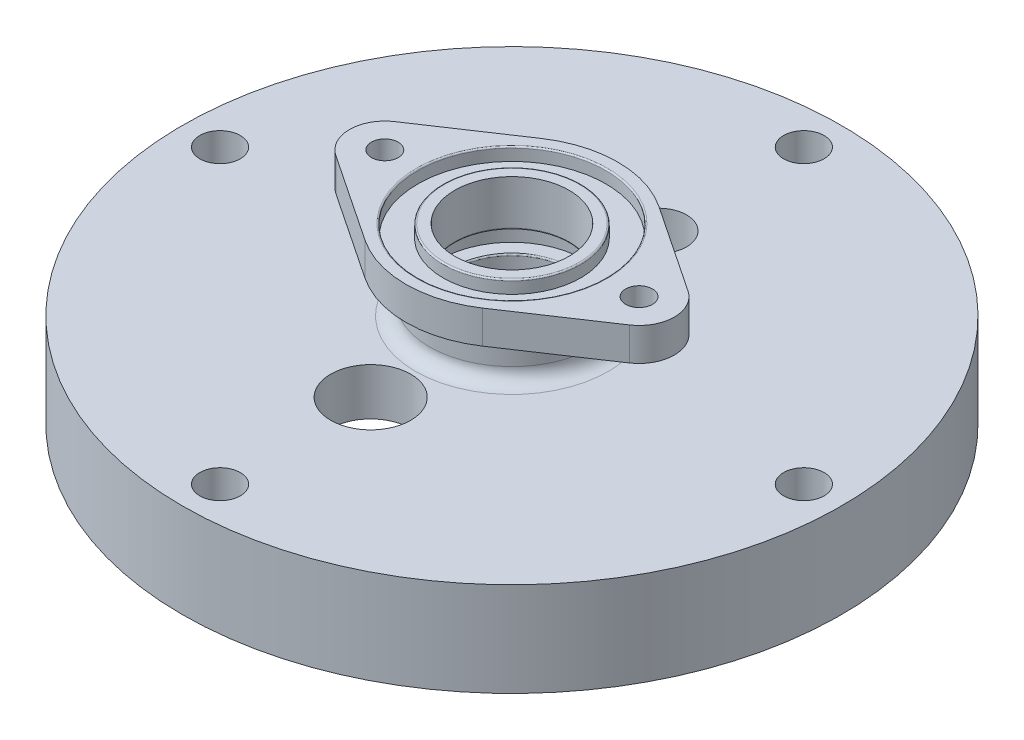
SolidWorks part; units mm, degrees
material "ABS"
ref_plane "Ön Düzlem" through (0, 0, 0) normal (0, 0, 1) x (1, 0, 0)
ref_plane "Üst Düzlem" through (0, 0, 0) normal (0, 1, 0) x (1, 0, 0)
ref_plane "Sağ Düzlem" through (0, 0, 0) normal (1, 0, 0) x (0, 0, -1)
sketch "Çizim1" plane through (0, 0, 0) normal (0, 1, 0) x (1, 0, 0)
  circle A0 centre (0, 0) radius 70
  dimension "D1" = 140
extrude "Yükseklik-Ekstrüzyon1" add sketch "Çizim1" along normal blind 20
sketch "Çizim2" plane through (0, 0, 0) normal (0, -1, 0) x (1, 0, 0)
  circle A0 centre (0, 0) radius 50.03
  circle A1 centre (0, 0) radius 45
  circle A2 centre (0, 0) radius 41
  circle A3 centre (0, 0) radius 17.35
  dimension "D1" = 100.06
  dimension "D2" = 90
  dimension "D3" = 82
  dimension "D4" = 34.7
extrude "Kes-Ekstrüzyon1" cut sketch "Çizim2" against normal blind 10 contours A0 A1 | A2 A3
sketch "Çizim4" plane through (0, 0, 0) normal (0, 0, 1) x (1, 0, 0)
  line L0 (-41, 0) -> (-13.6, 0)
  line L1 (-41, 0) -> (41, 0) construction
  line L2 (-45, 0) -> (45, 0) construction
  line L3 (-17.35, 0) -> (17.35, 0) construction
  line L4 (-17.35, 10) -> (-13.6, 0)
  line L8 (-17.35, 10) -> (17.35, 10) construction
  line L9 (-41, 10) -> (41, 10) construction
  line L10 (-17.35, 0) -> (-17.35, 10)
  line L11 (0, 0) -> (0, 30.5491)
  dimension "D1" = 27.4
revolve "Kes-Döndür1" cut sketch "Çizim4" angle 360 about L11
sketch "Çizim5" plane through (0, 20, 0) normal (0, 1, 0) x (1, 0, 0)
  circle A0 centre (0, 0) radius 17.5
  dimension "D1" = 35
extrude "Yükseklik-Ekstrüzyon2" add sketch "Çizim5" along normal blind 10
sketch "Çizim7" plane through (0, 30, 0) normal (0, 1, 0) x (1, 0, 0)
  line L2 (31.1667, -6.2361) -> (12.5, -18.7083)
  line L3 (31.1667, 6.2361) -> (12.5, 18.7083)
  line L4 (-12.5, -18.7083) -> (-31.1667, -6.2361)
  line L5 (-12.5, 18.7083) -> (-31.1667, 6.2361)
  arc A0 (12.5, 18.7083) -> (-12.5, 18.7083) centre (0, 0) ccw
  circle A1 centre (-27, 0) radius 2.85
  arc A2 (-31.1667, 6.2361) -> (-31.1667, -6.2361) centre (-27, 0) ccw
  circle A3 centre (27, 0) radius 2.85
  arc A4 (31.1667, -6.2361) -> (31.1667, 6.2361) centre (27, 0) ccw
  arc A5 (-12.5, -18.7083) -> (12.5, -18.7083) centre (0, 0) ccw
  dimension "D1" = 45
  dimension "D3" = 5.7
  dimension "D6" = 5.7
  dimension "D2" = 27
  dimension "D5" = 27
extrude "Yükseklik-Ekstrüzyon3" add sketch "Çizim7" along normal blind 7
sketch "Çizim8" plane through (0, 37, 0) normal (0, 1, 0) x (1, 0, 0)
  circle A0 centre (0, 0) radius 12.15
  dimension "D1" = 24.3
extrude "Kes-Ekstrüzyon3" cut sketch "Çizim8" against normal through all
sketch "Çizim9" plane through (0, 37, 0) normal (0, 1, 0) x (1, 0, 0)
  circle A1 centre (0, 0) radius 14.62
  circle A3 centre (0, 0) radius 19.98
  dimension "D1" = 39.96
  dimension "D2" = 29.24
extrude "Kes-Ekstrüzyon4" cut sketch "Çizim9" against normal blind 2.75
fillet "Radyus1" radius 0.3 2 edges at (0, 37, 14.62) (0, 37, 19.98)
fillet "Radyus2" radius 3 2 edges at (0, 30, 17.5) (0, 20, 17.5)
sketch "Çizim10" plane through (0, 0, 0) normal (0, 0, 1) x (1, 0, 0)
  line L1 (-11.9162, 27.2319) -> (-11.9162, 22.7319)
  line L4 (-11.9162, 22.7319) -> (-15.24, 22.7319)
  line L5 (-15.24, 22.7319) -> (-15.24, 27.2319)
  line L6 (-15.24, 27.2319) -> (-11.9162, 27.2319)
  line L7 (0, 0) -> (0, 39.8793)
  dimension "D1" = 15.24
revolve "Kes-Döndür2" cut sketch "Çizim10" angle 360 about L7
fillet "Radyus3" radius 0.3 2 edges at (0, 27.2319, 12.15) (0, 22.7319, -12.15)
sketch "Çizim11" plane through (0, 0, 0) normal (0, 0, 1) x (1, 0, 0)
  line L0 (-50, 7.375) -> (-50, 2.625)
  line L1 (-50, 2.625) -> (-52.75, 2.625)
  line L2 (-52.75, 2.625) -> (-52.75, 7.375)
  line L6 (-52.75, 7.375) -> (-50, 7.375)
  line L7 (0, 37) -> (0, -25.9971)
  line L8 (12.15, 37) -> (-12.15, 37) construction
  dimension "D1" = 2.75
  dimension "D2" = 4.75
  dimension "D3" = 50
sketch "Çizim12" plane through (0, 20, 0) normal (0, 1, 0) x (1, 0, 0)
  circle A2 centre (0, 62) radius 4.3
  circle A3 centre (62, 0) radius 4.3
  circle A4 centre (0, -62) radius 4.3
  circle A5 centre (-62, 0) radius 4.3
  point P15 (0, 0)
  dimension "D2" = 8.6
  dimension "D3" = 4
extrude "Kes-Ekstrüzyon5" cut sketch "Çizim12" against normal through all
sketch "Çizim13" plane through (0, 10, 0) normal (0, -1, 0) x (1, 0, 0)
  circle A0 centre (0, 30) radius 8.5
  dimension "D1" = 17
  dimension "D2" = 30
extrude "Kes-Ekstrüzyon6" cut sketch "Çizim13" against normal blind 14
sketch "Çizim14" plane through (0, 10, 0) normal (0, -1, 0) x (1, 0, 0)
  circle A0 centre (0, 0) radius 45
  circle A1 centre (0, 0) radius 50.03
extrude "Kes-Ekstrüzyon8" cut sketch "Çizim14" against normal blind 3
sketch "Çizim15" plane through (0, 10, 0) normal (0, -1, 0) x (1, 0, 0)
  circle A0 centre (0, -31.1905) radius 5.9
  dimension "D1" = 11.8
extrude "Kes-Ekstrüzyon9" cut sketch "Çizim15" against normal blind 10
